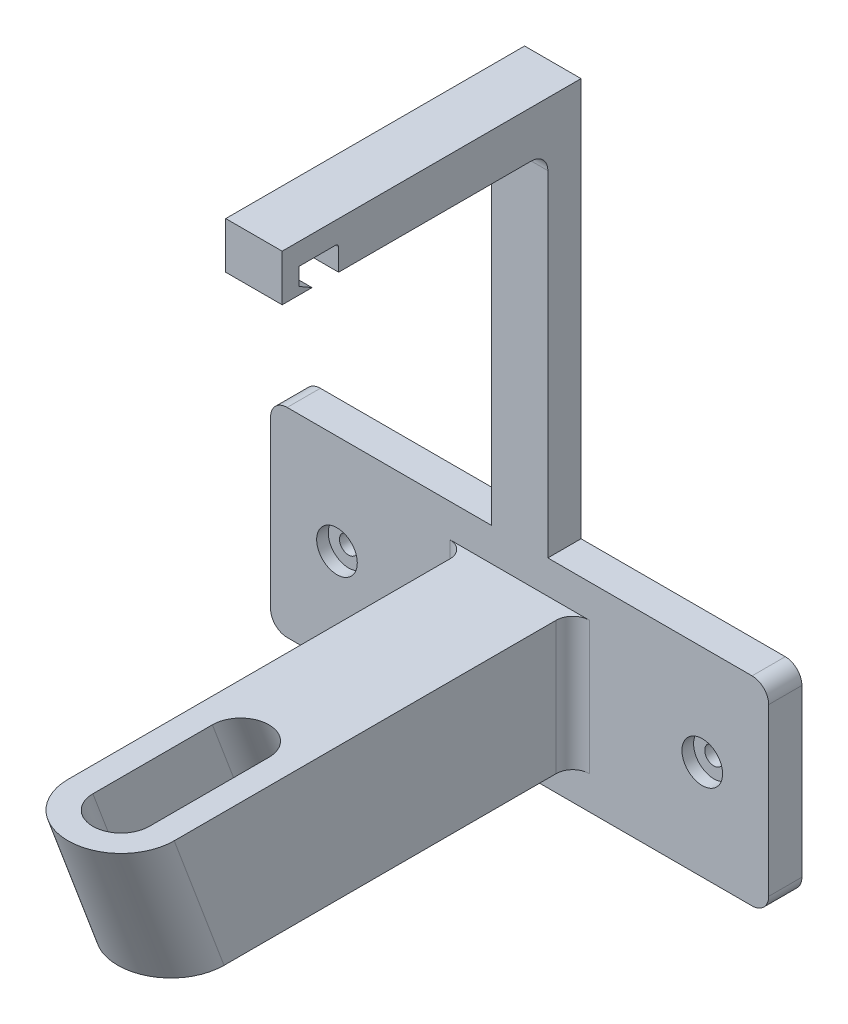
SolidWorks part; units mm, degrees
ref_plane "Front Plane" through (0, 0, 0) normal (0, 0, 1) x (1, 0, 0)
ref_plane "Top Plane" through (0, 0, 0) normal (0, 1, 0) x (1, 0, 0)
ref_plane "Right Plane" through (0, 0, 0) normal (1, 0, 0) x (0, 0, -1)
sketch "Sketch1" plane through (0, 0, 0) normal (0, 0, 1) x (1, 0, 0)
  line L1 (-75, 30) -> (75, 30)
  line L2 (-75, 30) -> (-75, -30)
  line L3 (-75, -30) -> (75, -30)
  line L4 (75, 30) -> (75, -30)
  line L5 (-75, 30) -> (75, -30) construction
  line L6 (-75, -30) -> (75, 30) construction
  point P0 (0, 0)
  dimension "D1" = 150
  dimension "D2" = 60
extrude "Boss-Extrude1" add sketch "Sketch1" along normal blind 10
hole_wizard "CBORE for M5 Hex Head Bolt1" positions "3DSketch1" profile "Sketch3" counterbore size "M5" standard "ISO" end condition through all
sketch3d "3DSketch1"
  line L0 (-75, 30, 10) -> (-75, -30, 10) construction
  line L1 (75, 30, 10) -> (-75, 30, 10) construction
  line L2 (75, -30, 10) -> (75, 30, 10) construction
  line L3 (-75, -30, 10) -> (75, -30, 10) construction
  point P0 (-55, 0, 10)
  point P2 (55, 0, 10)
  dimension "D1" = 20
  dimension "D2" = 30
  dimension "D3" = 20
  dimension "D4" = 30
sketch "Sketch3" plane through (-55, 0, 10) normal (1, 0, 0) x (0, -1, 0)
  line L0 (0, 0) -> (0, 10)
  line L1 (0, 10) -> (2.75, 10)
  line L3 (2.75, 10) -> (2.75, 3.5)
  line L4 (2.75, 3.5) -> (6.119, 3.5)
  line L5 (6.119, 3.5) -> (6.119, 0)
  line L7 (6.119, 0) -> (0, 0)
  line L11 (0, -6.35) -> (0, 107.95) construction
  dimension "Thru Hole Dia." = 5.5
  dimension "Thru Hole Depth" = 10
  dimension "C'Bore Dia." = 12.238
  dimension "C'Bore Depth" = 3.5
sketch "Sketch4" plane through (0, 0, 10) normal (0, 0, 1) x (1, 0, 0)
  line L1 (-16, 20) -> (16, 20)
  line L2 (-16, 20) -> (-16, -20)
  line L3 (-16, -20) -> (16, -20)
  line L4 (16, 20) -> (16, -20)
  line L5 (-16, 20) -> (16, -20) construction
  line L6 (-16, -20) -> (16, 20) construction
  point P0 (0, 0)
  dimension "D1" = 40
  dimension "D2" = 32
extrude "Boss-Extrude2" add sketch "Sketch4" along normal blind 120
sketch "Sketch7" plane through (16, 0, 0) normal (1, 0, 0) x (0, 0, -1)
  line L0 (-130, 20) -> (-115, -20)
  line L1 (-130, -20) -> (-10, -20) construction
  line L2 (-115, -20) -> (-130, -20)
  line L3 (-130, -20) -> (-130, 20)
  line L4 (-10, -30) -> (-10, 30) construction
  dimension "D1" = 105
extrude "Cut-Extrude1" cut sketch "Sketch7" against normal blind 120
sketch "Sketch8" plane through (0, 20, 0) normal (0, 1, 0) x (1, 0, 0)
  line L0 (16, -130) -> (-16, -130) construction
  line L1 (-16, -130) -> (16, -130)
  arc A0 (-16, -130) -> (16, -130) centre (0, -130) ccw
extrude "Boss-Extrude3" add sketch "Sketch8" along direction (0, 0.9363, 0.3511) on the side against the normal up to surface (40 mm away)
sketch "Sketch9" plane through (0, 20, 0) normal (0, 1, 0) x (1, 0, 0)
  line L0 (0, -94) -> (0, -130) construction
  line L1 (8.5, -94) -> (8.5, -130)
  line L2 (-8.5, -94) -> (-8.5, -130)
  line L4 (16, -130) -> (16, -10) construction
  line L5 (75, -10) -> (-75, -10) construction
  arc A0 (8.5, -94) -> (-8.5, -94) centre (0, -94) ccw
  arc A1 (-8.5, -130) -> (8.5, -130) centre (0, -130) ccw
  point P3 (0, -112)
  dimension "D1" = 8.5
  dimension "D2" = 36
  dimension "D3" = 16
  dimension "D4" = 84
extrude "Cut-Extrude2" cut sketch "Sketch9" along direction (0, 0.9363, 0.3511) on the side against the normal up to surface (42.72 mm away)
sketch "Sketch10" plane through (0, 30, 0) normal (0, 1, 0) x (1, 0, 0)
  line L0 (75, -10) -> (-75, -10) construction
  line L1 (-8.5, 0) -> (8.5, 0)
  line L2 (-8.5, 0) -> (-8.5, -10)
  line L3 (-8.5, -10) -> (8.5, -10)
  line L4 (8.5, 0) -> (8.5, -10)
  line L5 (-8.5, 0) -> (8.5, -10) construction
  line L6 (-8.5, -10) -> (8.5, 0) construction
  line L7 (-75, -10) -> (-75, 0) construction
  point P0 (0, -5)
  dimension "D1" = 17
  dimension "D2" = 75
  dimension "D3" = 10
extrude "Boss-Extrude4" add sketch "Sketch10" along normal blind 120
sketch "Sketch11" plane through (0, 0, 10) normal (0, 0, 1) x (1, 0, 0)
  line L0 (8.5, 150) -> (8.5, 30) construction
  line L1 (-8.5, 150) -> (8.5, 150)
  line L2 (-8.5, 150) -> (-8.5, 136)
  line L3 (-8.5, 136) -> (8.5, 136)
  line L4 (8.5, 150) -> (8.5, 136)
  dimension "D1" = 14
extrude "Boss-Extrude5" add sketch "Sketch11" along normal blind 80
sketch "Sketch13" plane through (8.5, 0, 0) normal (1, 0, 0) x (0, 0, -1)
  line L0 (-85, 143.5) -> (-85, 138.3094)
  line L1 (-85, 138.3094) -> (-81, 136)
  line L2 (-90, 136) -> (-10, 136) construction
  line L3 (-81, 136) -> (-73, 136)
  line L4 (-73, 136) -> (-73, 143.5)
  line L5 (-73, 143.5) -> (-85, 143.5)
  line L6 (-90, 136) -> (-90, 150) construction
  dimension "D1" = 5
  dimension "D2" = 30
  dimension "D3" = 12
  dimension "D4" = 8
  dimension "D5" = 4
  dimension "D6" = 7.5
extrude "Cut-Extrude3" cut sketch "Sketch13" against normal blind 95
fillet "Fillet1" radius 5 1 edges at (0, 136, 10)
fillet "Fillet2" radius 5 4 edges at (75, -30, 5) (75, 30, 5) (-75, -30, 5) (-75, 30, 5)
fillet "Fillet3" radius 5 2 edges at (-16, 0, 10) (16, 0, 10)
fillet "Fillet4" radius 1 1 edges at (0, 143.5, 73)
